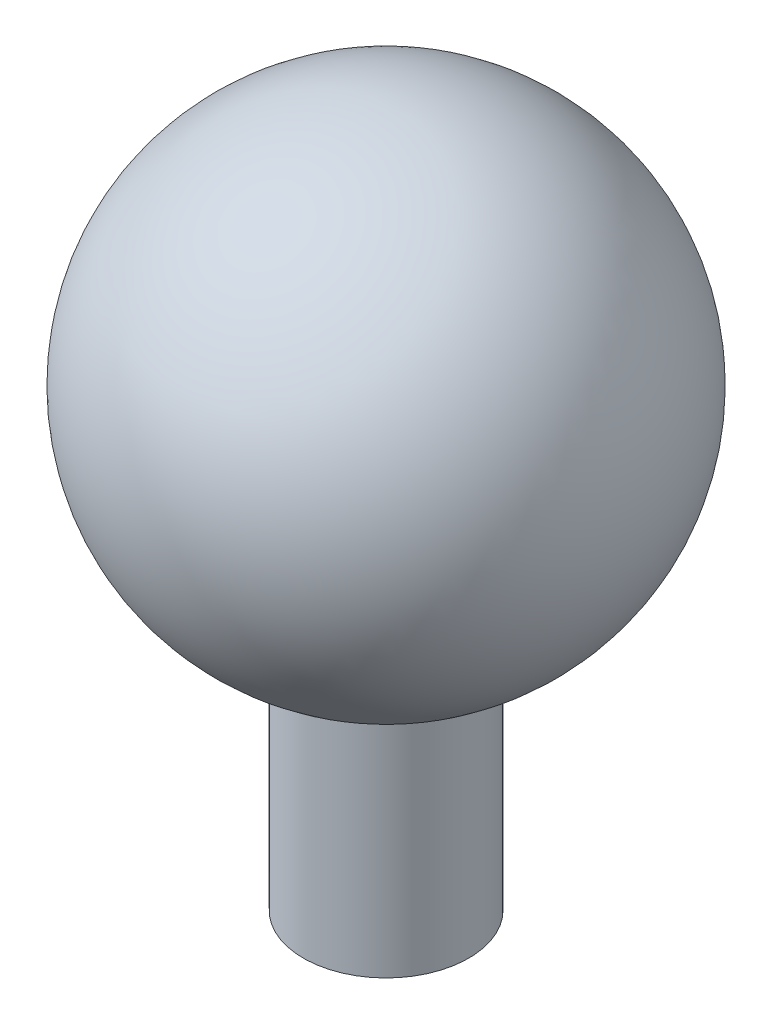
SolidWorks part; units mm, degrees
material "Cast Alloy Steel"
ref_plane "Front Plane" through (0, 0, 0) normal (0, 0, 1) x (1, 0, 0)
ref_plane "Top Plane" through (0, 0, 0) normal (0, 1, 0) x (1, 0, 0)
ref_plane "Right Plane" through (0, 0, 0) normal (1, 0, 0) x (0, 0, -1)
sketch "Sketch1" plane through (0, 0, 0) normal (0, 0, 1) x (1, 0, 0)
  line L0 (0, 29) -> (0, -29)
  arc A0 (0, -29) -> (0, 29) centre (0, 0) ccw
  point P4 (0, 0)
  dimension "D1" = 58
revolve "Revolve1" add sketch "Sketch1" angle 360 about L0
sketch "Sketch3" plane through (0, 0, 0) normal (0, 0, 1) x (1, 0, 0)
  line L0 (0, -30) -> (0, -55)
  line L1 (0, -55) -> (10, -55)
  line L2 (10, -55) -> (10, -27.2213)
  circle A0 centre (0, 0) radius 29 construction
  arc A1 (0, -30) -> (10, -27.2213) centre (-2.9107, -0.1415) ccw
  dimension "D1" = 30
  dimension "D2" = 25
  dimension "D3" = 10
revolve "Revolve2" add sketch "Sketch3" angle 360 about L0
